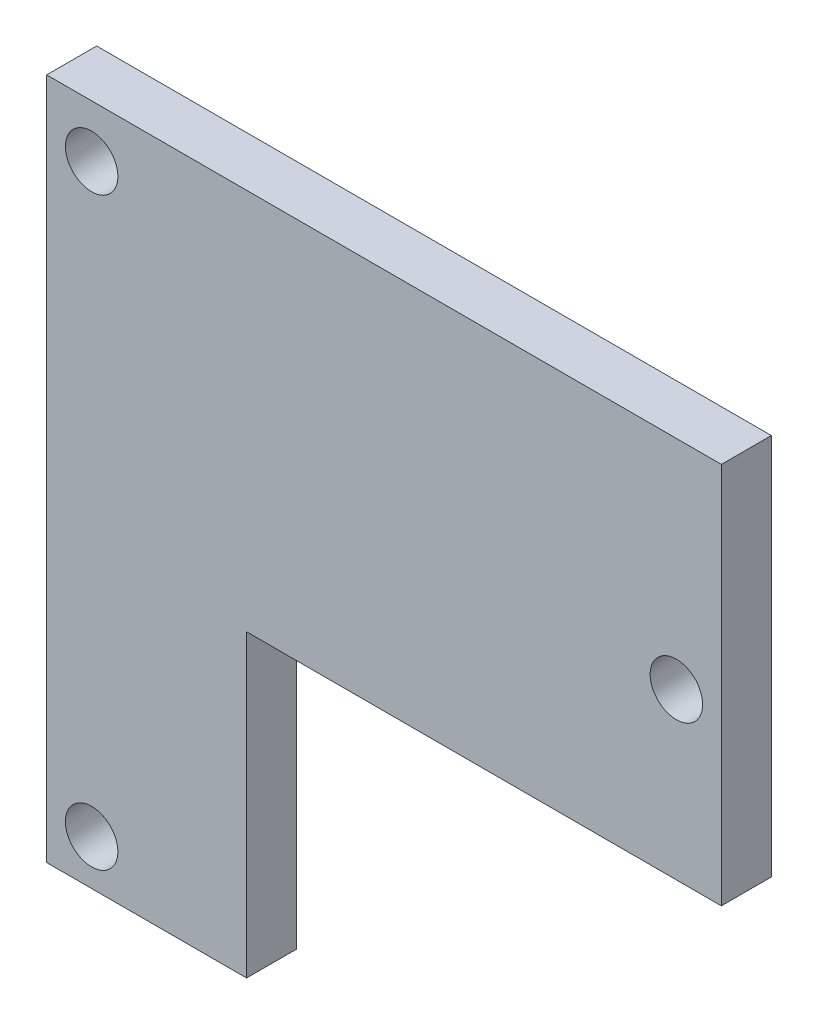
SolidWorks part; units mm, degrees
ref_plane "Front Plane" through (0, 0, 0) normal (0, 0, 1) x (1, 0, 0)
ref_plane "Top Plane" through (0, 0, 0) normal (0, 1, 0) x (1, 0, 0)
ref_plane "Right Plane" through (0, 0, 0) normal (1, 0, 0) x (0, 0, -1)
sketch "Sketch1" plane through (0, 0, 0) normal (0, 0, 1) x (1, 0, 0)
  line L0 (-51.85, -32.1) -> (-51.85, -55.5) construction
  line L1 (-51.85, -55.5) -> (-51.85, -57.3) construction
  line L2 (-51.85, -57.3) -> (-53.65, -57.3) construction
  line L3 (-50.65, -30) -> (-26.15, -30) construction
  line L4 (-53.65, -57.3) -> (-45.65, -57.3)
  line L5 (-53.65, -57.3) -> (-53.65, -30)
  line L6 (-53.65, -30) -> (-26.65, -30)
  line L7 (-26.65, -45.3) -> (-26.65, -30)
  line L8 (-53.65, -57.3) -> (-45.65, -57.3) construction
  line L9 (-45.65, -57.3) -> (-45.65, -45.3)
  line L10 (-45.65, -45.3) -> (-26.65, -45.3)
  circle A0 centre (-28.45, -38.7) radius 1.05
  circle A1 centre (-51.85, -32.1) radius 1.05
  circle A2 centre (-51.85, -55.5) radius 1.05
  dimension "D5" = 2.1
  dimension "D6" = 2.1
  dimension "D7" = 2.1
  dimension "D1" = 23.4
  dimension "D2" = 1.8
  dimension "D3" = 1.8
  dimension "D4" = 27
  dimension "D8" = 8
  dimension "D9" = 12
extrude "Boss-Extrude1" add sketch "Sketch1" along normal blind 2
